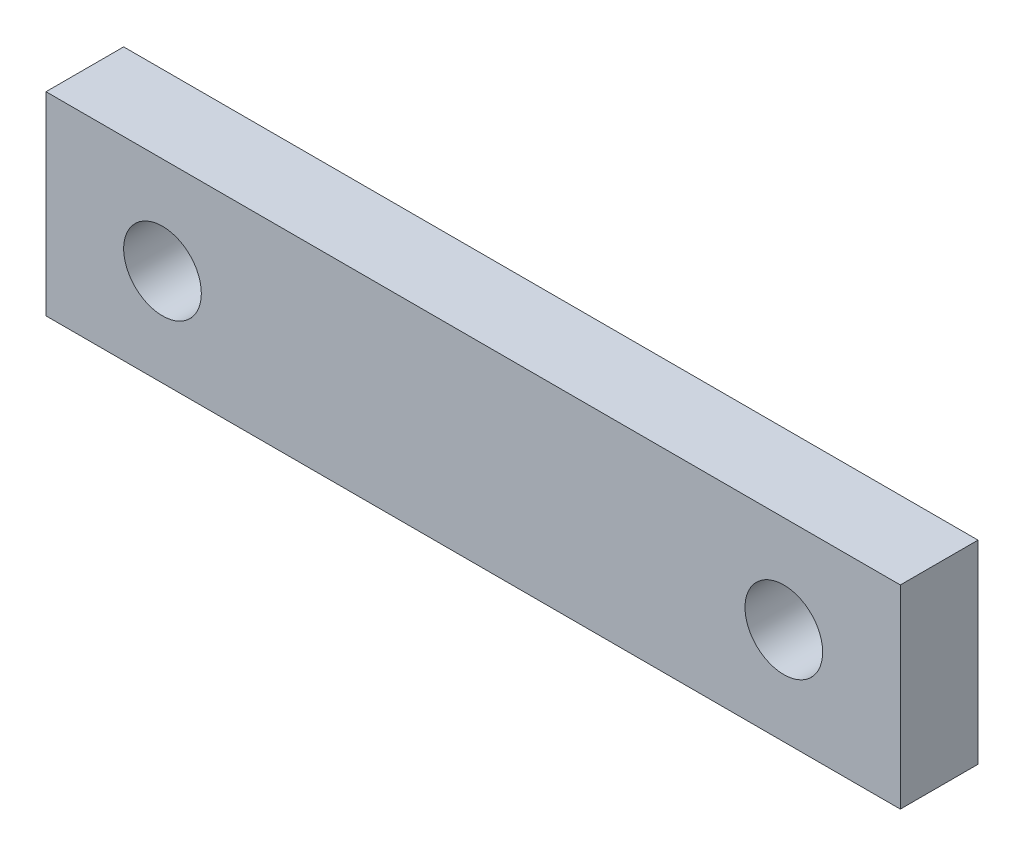
SolidWorks part; units mm, degrees
ref_plane "Front Plane" through (0, 0, 0) normal (0, 0, 1) x (1, 0, 0)
ref_plane "Top Plane" through (0, 0, 0) normal (0, 1, 0) x (1, 0, 0)
ref_plane "Right Plane" through (0, 0, 0) normal (1, 0, 0) x (0, 0, -1)
sketch "Sketch1" plane through (0, 0, 0) normal (0, 0, 1) x (1, 0, 0)
  line L1 (-62.9568, 47.7044) -> (216.4432, 47.7044)
  line L2 (-62.9568, 47.7044) -> (-62.9568, -15.7956)
  line L3 (-62.9568, -15.7956) -> (216.4432, -15.7956)
  line L4 (216.4432, 47.7044) -> (216.4432, -15.7956)
extrude "Boss-Extrude1" add sketch "Sketch1" along normal blind 25.4
sketch "Sketch4" plane through (0, 0, 25.4) normal (0, 0, 1) x (1, 0, 0)
  line L0 (-62.9568, 47.7044) -> (-62.9568, -15.7956) construction
  line L1 (216.4432, 47.7044) -> (-62.9568, 47.7044) construction
  circle A0 centre (-24.8568, 15.9544) radius 12.7
  point P6 (0, 0)
  dimension "D1" = 38.1
  dimension "D2" = 31.75
sketch "Sketch5" plane through (0, 0, 25.4) normal (0, 0, 1) x (1, 0, 0)
  line L0 (216.4432, -15.7956) -> (216.4432, 47.7044) construction
  line L1 (216.4432, 47.7044) -> (-62.9568, 47.7044) construction
  circle A0 centre (178.3432, 15.9544) radius 12.7
  dimension "D1" = 38.1
  dimension "D2" = 31.75
extrude "Cut-Extrude2" cut sketch "Sketch5" against normal through all
extrude "Cut-Extrude3" cut sketch "Sketch4" against normal through all contours A0
